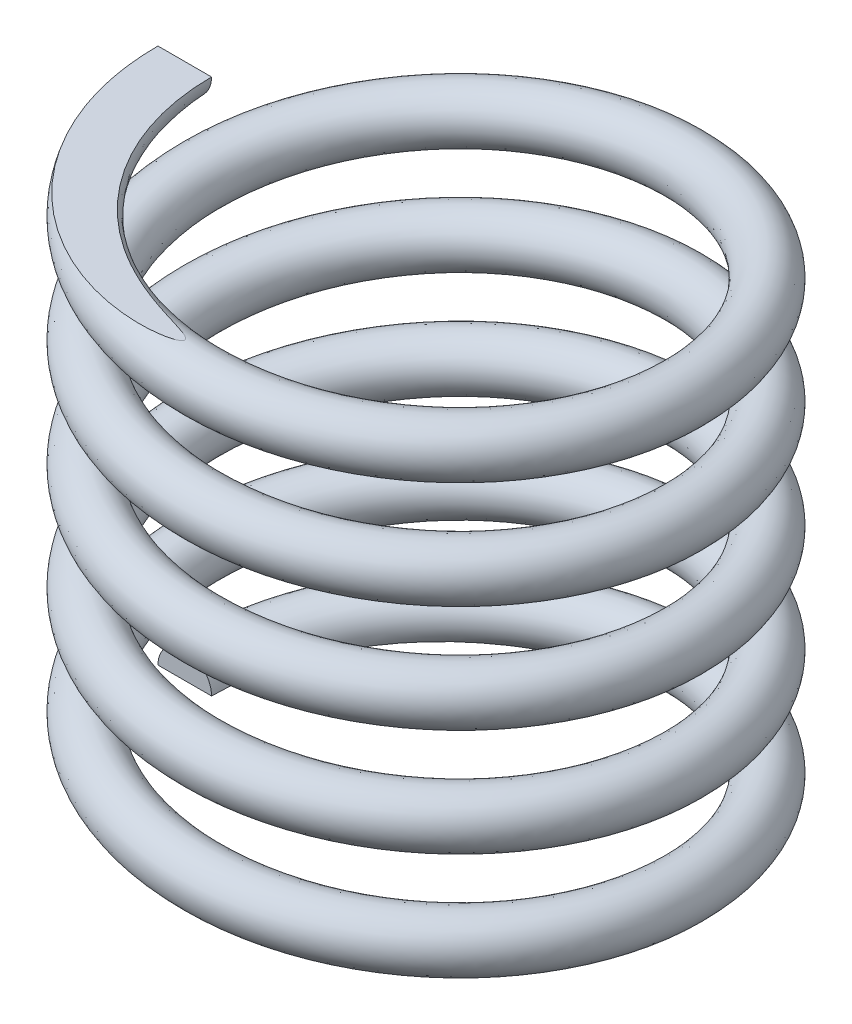
SolidWorks part; units mm, degrees
ref_plane "Front Plane" through (0, 0, 0) normal (0, 0, 1) x (1, 0, 0)
ref_plane "Top Plane" through (0, 0, 0) normal (0, 1, 0) x (1, 0, 0)
ref_plane "Right Plane" through (0, 0, 0) normal (1, 0, 0) x (0, 0, -1)
sketch "Sketch1" plane through (0, 0, 0) normal (0, 1, 0) x (1, 0, 0)
  circle A0 centre (0, 0) radius 9
  dimension "D1" = 18
curve "Helix/Spiral1" pitch 4 height 20 turns 5
sketch "Sketch2" plane through (0, 0, 0) normal (0, 0, 1) x (1, 0, 0)
  circle A0 centre (-9, 0) radius 1
  spline S0 degree 3 poles (-9, 0) (-9, 0.0828) (-8.5314, 0.2502) (-6.5296, 0.4999) (-3.5338, 0.75) (0, 1) (3.5338, 1.25) (6.5296, 1.5) (8.5314, 1.75) (9.2343, 2) (8.5314, 2.25) (6.5296, 2.5) (2.5352, 2.8333) (-2.5352, 3.1667) (-6.5296, 3.5) (-8.5314, 3.75) (-9.2343, 4) (-8.5314, 4.25) (-6.5296, 4.5) (-2.5352, 4.8333) (2.5352, 5.1667) (6.5296, 5.5) (8.5314, 5.75) (9.2343, 6) (8.5314, 6.25) (6.5296, 6.5) (2.5352, 6.8333) (-2.5352, 7.1667) (-6.5296, 7.5) (-8.5314, 7.75) (-9.2343, 8) (-8.5314, 8.25) (-6.5296, 8.5) (-2.5352, 8.8333) (2.5352, 9.1667) (6.5296, 9.5) (8.5314, 9.75) (9.2343, 10) (8.5314, 10.25) (6.5296, 10.5) (2.5352, 10.8333) (-2.5352, 11.1667) (-6.5296, 11.5) (-8.5314, 11.75) (-9.2343, 12) (-8.5314, 12.25) (-6.5296, 12.5) (-2.5352, 12.8333) (2.5352, 13.1667) (6.5296, 13.5) (8.5314, 13.75) (9.2343, 14) (8.5314, 14.25) (6.5296, 14.5) (2.5352, 14.8333) (-2.5352, 15.1667) (-6.5296, 15.5) (-8.5314, 15.75) (-9.2343, 16) (-8.5314, 16.25) (-6.5296, 16.5) (-2.5352, 16.8333) (2.5352, 17.1667) (6.5296, 17.5) (8.5314, 17.75) (9.2343, 18) (8.5314, 18.25) (6.5296, 18.5) (3.5338, 18.75) (0, 19) (-3.5338, 19.25) (-6.5296, 19.5001) (-8.5314, 19.7498) (-9, 19.9172) (-9, 20) knots 0 0 0 0 0.0125 0.025 0.0375 0.05 0.0625 0.075 0.0875 0.1 0.1125 0.125 0.1375 0.1625 0.175 0.1875 0.2 0.2125 0.225 0.2375 0.2625 0.275 0.2875 0.3 0.3125 0.325 0.3375 0.3625 0.375 0.3875 0.4 0.4125 0.425 0.4375 0.4625 0.475 0.4875 0.5 0.5125 0.525 0.5375 0.5625 0.575 0.5875 0.6 0.6125 0.625 0.6375 0.6625 0.675 0.6875 0.7 0.7125 0.725 0.7375 0.7625 0.775 0.7875 0.8 0.8125 0.825 0.8375 0.8625 0.875 0.8875 0.9 0.9125 0.925 0.9375 0.95 0.9625 0.975 0.9875 1 1 1 1 construction
  dimension "D1" = 2
sweep "Sweep1" add profiles "Sketch2" path "Helix/Spiral1"
sketch "Sketch3" plane through (0, 0, 0) normal (0, 0, 1) x (1, 0, 0)
  line L1 (-11.0621, 0) -> (12.3509, 0)
  line L2 (-11.0621, 0) -> (-11.0621, -2.1564)
  line L3 (-11.0621, -2.1564) -> (12.3509, -2.1564)
  line L4 (12.3509, 0) -> (12.3509, -2.1564)
  line L5 (-11.0621, 20) -> (13.049, 20)
  line L6 (-11.0621, 20) -> (-11.0621, 22.3628)
  line L7 (-11.0621, 22.3628) -> (13.049, 22.3628)
  line L8 (13.049, 20) -> (13.049, 22.3628)
  dimension "D1" = 20
extrude "Cut-Extrude1" cut sketch "Sketch3" against normal through all both and the other way through all
